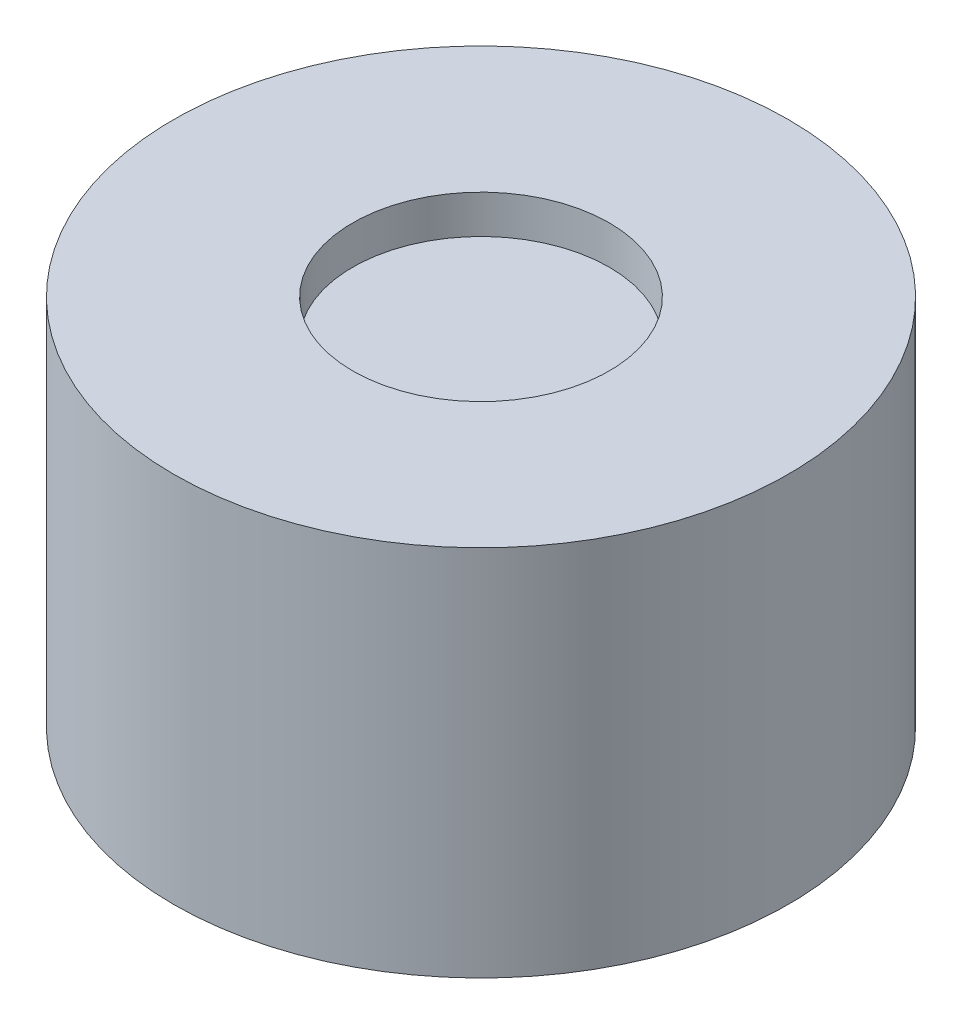
SolidWorks part; units mm, degrees
material "Aleación 6061"
ref_plane "Alzado" through (0, 0, 0) normal (0, 0, 1) x (1, 0, 0)
ref_plane "Planta" through (0, 0, 0) normal (0, 1, 0) x (1, 0, 0)
ref_plane "Vista lateral" through (0, 0, 0) normal (1, 0, 0) x (0, 0, -1)
sketch "Croquis1" plane through (0, 0, 0) normal (0, 1, 0) x (1, 0, 0)
  circle A0 centre (0, 0) radius 40
  dimension "D1" = 80
extrude "Saliente-Extruir1" add sketch "Croquis1" along normal blind 48.5
sketch "Croquis2" plane through (0, 48.5, 0) normal (0, 1, 0) x (1, 0, 0)
  circle A0 centre (0, 0) radius 16.7
  dimension "D1" = 33.4
extrude "Cortar-Extruir1" cut sketch "Croquis2" against normal blind 5
